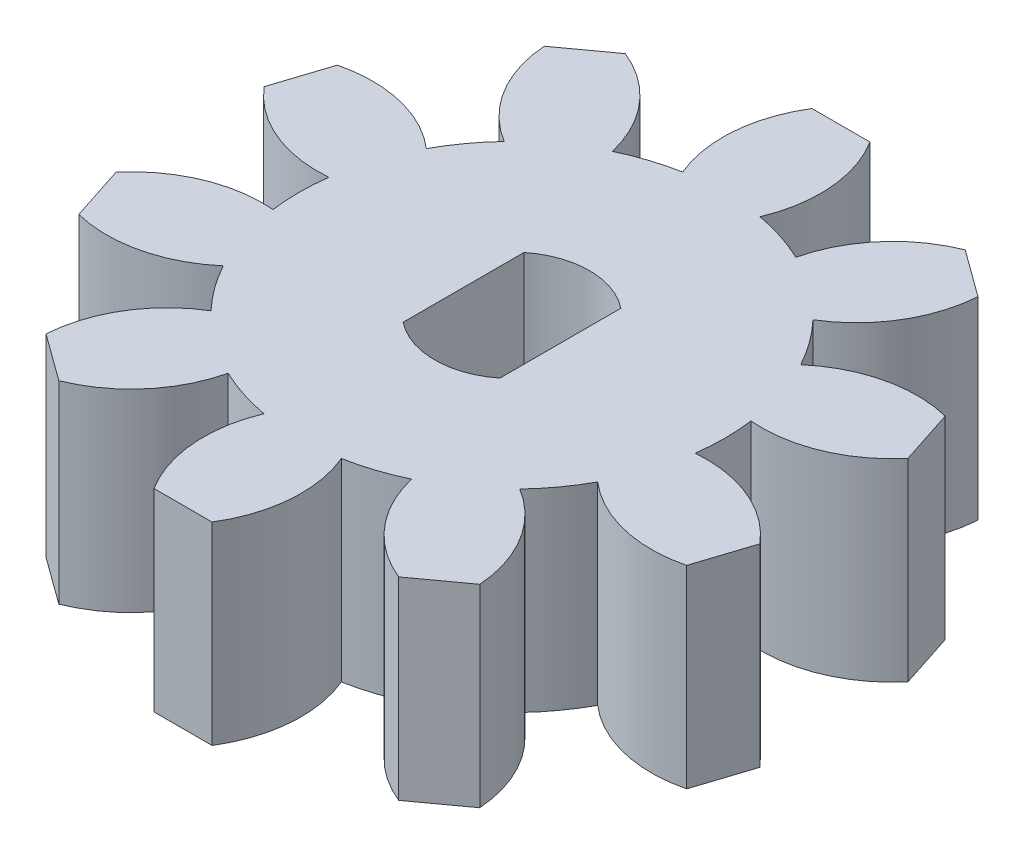
SolidWorks part; units mm, degrees
ref_plane "前视基准面" through (0, 0, 0) normal (0, 0, 1) x (1, 0, 0)
ref_plane "上视基准面" through (0, 0, 0) normal (0, 1, 0) x (1, 0, 0)
ref_plane "右视基准面" through (0, 0, 0) normal (1, 0, 0) x (0, 0, -1)
sketch "草图1" plane through (0, 0, 0) normal (0, 1, 0) x (1, 0, 0)
  circle A0 centre (0, 0) radius 5.5
extrude "凸台-拉伸1" add sketch "草图1" along normal blind 5
sketch "草图2" plane through (0, 5, 0) normal (0, 1, 0) x (-1, 0, 0)
  line L0 (-4.3894, -7.3175) -> (-5.6029, -6.4358)
  line L1 (-7.8522, -3.3399) -> (-8.3157, -1.9134)
  line L2 (-8.3157, 1.9134) -> (-7.8522, 3.3399)
  line L3 (-5.6029, 6.4358) -> (-4.3894, 7.3175)
  line L4 (-0.75, 8.5) -> (0.75, 8.5)
  line L5 (4.3894, 7.3175) -> (5.6029, 6.4358)
  line L6 (0.75, -8.5) -> (-0.75, -8.5)
  line L7 (7.8522, 3.3399) -> (8.3157, 1.9134)
  line L8 (8.3157, -1.9134) -> (7.8522, -3.3399)
  line L9 (5.6029, -6.4358) -> (4.3894, -7.3175)
  arc A0 (-1, -5.4083) -> (1, -5.4083) centre (0, 0) ccw
  arc A1 (-1, -5.4083) -> (-0.75, -8.5) centre (2.1122, -6.7126) ccw
  arc A2 (1, -5.4083) -> (0.75, -8.5) centre (-2.1122, -6.7126) cw
  arc A3 (-3.988, -3.7876) -> (-2.3699, -4.9632) centre (0, 0) ccw
  arc A4 (-3.988, -3.7876) -> (-5.6029, -6.4358) centre (-2.2368, -6.6721) ccw
  arc A5 (-2.3699, -4.9632) -> (-4.3894, -7.3175) centre (-5.6543, -4.1891) cw
  arc A6 (-5.4526, -0.7202) -> (-4.8346, -2.6223) centre (0, 0) ccw
  arc A7 (-5.4526, -0.7202) -> (-8.3157, -1.9134) centre (-5.7314, -4.0831) ccw
  arc A8 (-4.8346, -2.6223) -> (-7.8522, -3.3399) centre (-7.0368, -0.0655) cw
  arc A9 (-4.8346, 2.6223) -> (-5.4526, 0.7202) centre (0, 0) ccw
  arc A10 (-4.8346, 2.6223) -> (-7.8522, 3.3399) centre (-7.0368, 0.0655) ccw
  arc A11 (-5.4526, 0.7202) -> (-8.3157, 1.9134) centre (-5.7314, 4.0831) cw
  arc A12 (-2.3699, 4.9632) -> (-3.988, 3.7876) centre (0, 0) ccw
  arc A13 (-2.3699, 4.9632) -> (-4.3894, 7.3175) centre (-5.6543, 4.1891) ccw
  arc A14 (-3.988, 3.7876) -> (-5.6029, 6.4358) centre (-2.2368, 6.6721) cw
  arc A15 (1, 5.4083) -> (-1, 5.4083) centre (0, 0) ccw
  arc A16 (1, 5.4083) -> (0.75, 8.5) centre (-2.1122, 6.7126) ccw
  arc A17 (-1, 5.4083) -> (-0.75, 8.5) centre (2.1122, 6.7126) cw
  arc A18 (3.988, 3.7876) -> (2.3699, 4.9632) centre (0, 0) ccw
  arc A19 (3.988, 3.7876) -> (5.6029, 6.4358) centre (2.2368, 6.6721) ccw
  arc A20 (2.3699, 4.9632) -> (4.3894, 7.3175) centre (5.6543, 4.1891) cw
  arc A21 (5.4526, 0.7202) -> (4.8346, 2.6223) centre (0, 0) ccw
  arc A22 (5.4526, 0.7202) -> (8.3157, 1.9134) centre (5.7314, 4.0831) ccw
  arc A23 (4.8346, 2.6223) -> (7.8522, 3.3399) centre (7.0368, 0.0655) cw
  arc A24 (4.8346, -2.6223) -> (5.4526, -0.7202) centre (0, 0) ccw
  arc A25 (4.8346, -2.6223) -> (7.8522, -3.3399) centre (7.0368, -0.0655) ccw
  arc A26 (5.4526, -0.7202) -> (8.3157, -1.9134) centre (5.7314, -4.0831) cw
  arc A27 (2.3699, -4.9632) -> (3.988, -3.7876) centre (0, 0) ccw
  arc A28 (2.3699, -4.9632) -> (4.3894, -7.3175) centre (5.6543, -4.1891) ccw
  arc A29 (3.988, -3.7876) -> (5.6029, -6.4358) centre (2.2368, -6.6721) cw
  point P5 (0, -8.5)
  point P13 (-4.9962, -6.8766)
  point P22 (-8.084, -2.6266)
  point P30 (-8.084, 2.6266)
  point P38 (-4.9962, 6.8766)
  point P46 (0, 8.5)
  point P54 (4.9962, 6.8766)
  point P62 (8.084, 2.6266)
  point P70 (8.084, -2.6266)
  point P78 (4.9962, -6.8766)
  dimension "D1" = 10
extrude "凸台-拉伸2" add sketch "草图2" against normal up to surface (5 mm away) up to face at (0, 0, 5.5)
sketch "草图3" plane through (0, 5, 0) normal (0, 1, 0) x (-1, 0, 0)
  line L2 (1.25, -1.5612) -> (1.25, 1.5612)
  line L4 (-1.25, -1.5612) -> (-1.25, 1.5612)
  arc A0 (1.25, 1.5612) -> (-1.25, 1.5612) centre (0, 0) ccw
  arc A1 (-1.25, -1.5612) -> (1.25, -1.5612) centre (0, 0) ccw
extrude "切除-拉伸1" cut sketch "草图3" against normal up to next
